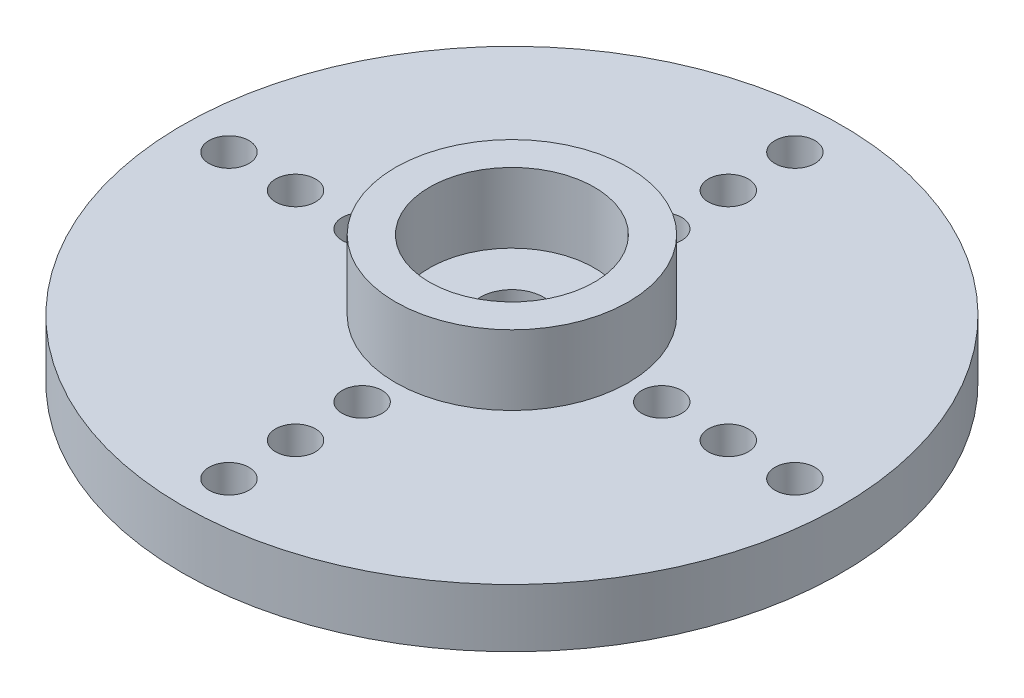
SolidWorks part; units mm, degrees
ref_plane "Plan de face" through (0, 0, 0) normal (0, 0, 1) x (1, 0, 0)
ref_plane "Plan de dessus" through (0, 0, 0) normal (0, 1, 0) x (1, 0, 0)
ref_plane "Plan de droite" through (0, 0, 0) normal (1, 0, 0) x (0, 0, -1)
sketch "Esquisse1" plane through (0, 0, 0) normal (0, 1, 0) x (1, 0, 0)
  circle A0 centre (0, 0) radius 9.9
  dimension "D1" = 19.8
extrude "Boss.-Extru.1" add sketch "Esquisse1" along normal blind 1.75
sketch "Esquisse2" plane through (0, 1.75, 0) normal (0, 1, 0) x (1, 0, 0)
  circle A0 centre (0, 0) radius 3.5
  circle A1 centre (0, 0) radius 2.475
  dimension "D1" = 7
  dimension "D2" = 4.95
extrude "Boss.-Extru.2" add sketch "Esquisse2" along normal blind 2.1
sketch "Esquisse3" plane through (0, 0, 0) normal (0, -1, 0) x (1, 0, 0)
  circle A0 centre (0, 0) radius 2.725
  circle A1 centre (0, 0) radius 2.225
  dimension "D1" = 5.45
  dimension "D2" = 0.5
extrude "Boss.-Extru.3" add sketch "Esquisse3" along normal blind 0.3
sketch "Esquisse4" plane through (0, 0, 0) normal (0, -1, 0) x (1, 0, 0)
  circle A0 centre (0, 0) radius 0.95
  dimension "D1" = 1.9
extrude "Enlèv. mat.-Extru.1" cut sketch "Esquisse4" against normal through all
sketch "Esquisse5" plane through (0, 0, 0) normal (0, -1, 0) x (1, 0, 0)
  line L0 (0, 0) -> (0, 9.9) construction
  circle A1 centre (0, 0) radius 9.9 construction
  circle A2 centre (0, 4.5) radius 0.6
  circle A3 centre (0, 6.5) radius 0.6
  circle A4 centre (0, 8.5) radius 0.6
  dimension "D4" = 1.2
  dimension "D1" = 2
  dimension "D2" = 2
  dimension "D3" = 4.5
extrude "Enlèv. mat.-Extru.2" cut sketch "Esquisse5" against normal through all
pattern_circular "Répétition circulaire1" count 4 over 360 about axis through (0, 0, 0) along (0, 1, 0) of "Enlèv. mat.-Extru.2"
